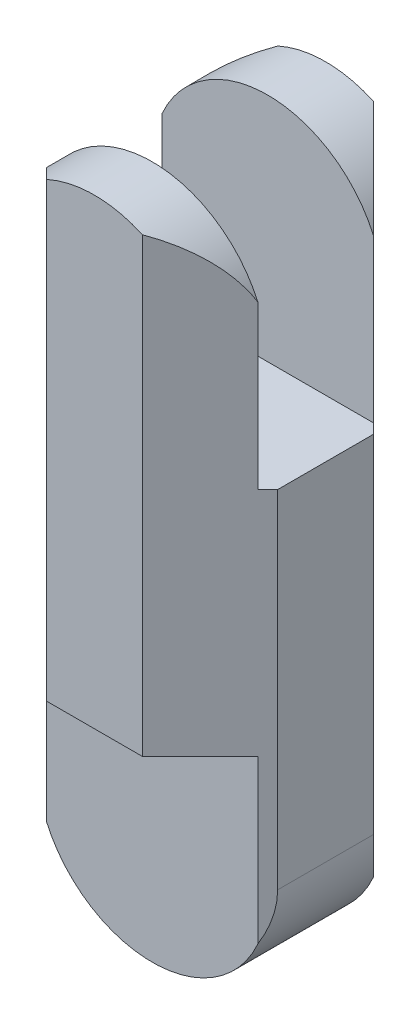
SolidWorks part; units mm, degrees
ref_plane "Front" through (0, 0, 0) normal (0, 0, 1) x (1, 0, 0)
ref_plane "Top" through (0, 0, 0) normal (0, 1, 0) x (1, 0, 0)
ref_plane "Right" through (0, 0, 0) normal (1, 0, 0) x (0, 0, -1)
sketch "草图1" plane through (0, 0, 0) normal (0, 1, 0) x (1, 0, 0)
  line L0 (-12.6518, 0) -> (13.462, 0) construction
  line L1 (0, 11.6722) -> (0, -14.1269) construction
  line L3 (10, 4.1421) -> (4.1421, 10)
  line L4 (4.1421, 10) -> (-4.1421, 10)
  line L5 (-4.1421, 10) -> (-10, 4.1421)
  line L6 (-10, 4.1421) -> (-10, -4.1421)
  line L7 (-10, -4.1421) -> (-4.1421, -10)
  line L8 (-4.1421, -10) -> (4.1421, -10)
  line L9 (4.1421, -10) -> (10, -4.1421)
  line L10 (10, -4.1421) -> (10, 4.1421)
  circle A0 centre (0, 0) radius 10 construction
extrude "凸台-拉伸1" add sketch "草图1" along normal blind 60
sketch "草图2" plane through (0, 0, 10) normal (0, 0, 1) x (1, 0, 0)
  line L0 (0, 0) -> (0, 24) construction
  line L7 (-10, 10) -> (-10, -2.3893)
  line L8 (-10, -2.3893) -> (10, -2.3893)
  line L9 (10, 10) -> (10, -2.3893)
  arc A1 (-10, 10) -> (10, 10) centre (0, 10) ccw
extrude "切除-拉伸1" cut sketch "草图2" against normal blind 66
sketch "草图4" plane through (0, 0, 10) normal (0, 0, 1) x (1, 0, 0)
  line L0 (10, 60) -> (10, 10) construction
  line L2 (-10, 10) -> (-10, 20)
  line L3 (-10, 20) -> (10, 20)
  line L4 (10, 10) -> (10, 20)
  arc A0 (-10, 10) -> (10, 10) centre (0, 10) ccw
extrude "切除-拉伸2" cut sketch "草图4" against normal blind 5
sketch "草图5" plane through (0, 0, -10) normal (0, 0, -1) x (-1, 0, 0)
  line L0 (10, 60) -> (10, 10) construction
  line L2 (-10, 10) -> (-10, 20)
  line L3 (-10, 20) -> (10, 20)
  line L4 (10, 10) -> (10, 20)
  arc A0 (-10, 10) -> (10, 10) centre (0, 10) ccw
extrude "切除-拉伸3" cut sketch "草图5" against normal blind 5
sketch "草图6" plane through (0, 0, 0) normal (0, 0, 1) x (1, 0, 0)
  line L0 (0, 60) -> (0, 0) construction
  line L1 (-4.1421, 60) -> (4.1421, 60) construction
  line L2 (10, 60) -> (10, 10) construction
  line L3 (-10, 60) -> (10, 60)
  line L4 (-10, 60) -> (-10, 40)
  line L5 (-10, 40) -> (10, 40)
  line L6 (10, 60) -> (10, 40)
  dimension "D1" = 20
extrude "切除-拉伸4" cut sketch "草图6" against normal mid plane 10
sketch "草图7" plane through (0, 0, 10) normal (0, 0, 1) x (1, 0, 0)
  line L0 (0, 60) -> (0, 0) construction
  line L1 (-4.1421, 60) -> (4.1421, 60) construction
  line L4 (-10, 50) -> (-10, 63.6612)
  line L5 (-10, 63.6612) -> (10, 63.6612)
  line L6 (10, 50) -> (10, 63.6612)
  arc A0 (10, 50) -> (-10, 50) centre (0, 50) ccw
extrude "切除-拉伸5" cut sketch "草图7" against normal blind 30
